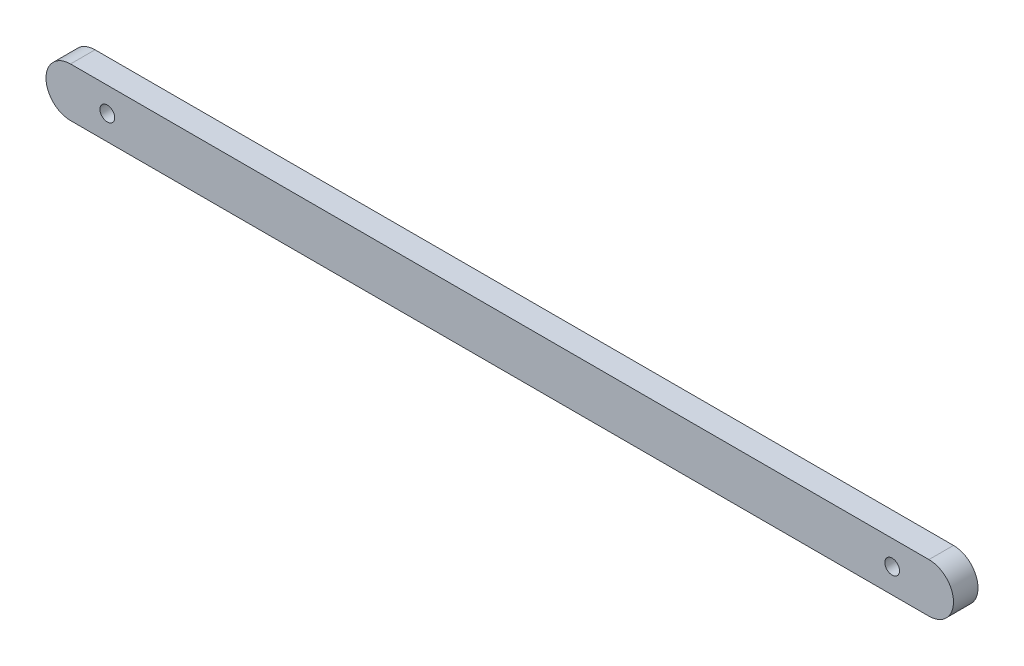
SolidWorks part; units mm, degrees
material "1023 Carbon Steel Sheet (SS)"
ref_plane "Ön Düzlem" through (0, 0, 0) normal (0, 0, 1) x (1, 0, 0)
ref_plane "Üst Düzlem" through (0, 0, 0) normal (0, 1, 0) x (1, 0, 0)
ref_plane "Sağ Düzlem" through (0, 0, 0) normal (1, 0, 0) x (0, 0, -1)
sketch "Sketch1" plane through (0, 0, 0) normal (0, 0, 1) x (1, 0, 0)
  line L4 (-175, 0) -> (175, 0) construction
  line L5 (-175, 10) -> (175, 10)
  line L6 (-175, -10) -> (175, -10)
  arc A0 (-175, 10) -> (-175, -10) centre (-175, 0) ccw
  arc A1 (175, -10) -> (175, 10) centre (175, 0) ccw
  point P3 (0, 0)
  point P8 (0, 0)
  dimension "D1" = 10
  dimension "D2" = 350
extrude "Boss-Extrude2" add sketch "Sketch1" along normal blind 10 contours A0 L6 A1 L5
sketch "Sketch3" plane through (0, 0, 10) normal (0, 0, 1) x (1, 0, 0)
  line L0 (-175, -10) -> (175, -10) construction
  line L2 (0, 0) -> (0, -10) construction
  circle A0 centre (-160, 0) radius 3
  arc A2 (-175, 10) -> (-175, -10) centre (-175, 0) ccw construction
  circle A3 centre (160, 0) radius 3
  point P5 (-185, 0)
  dimension "D1" = 6
  dimension "D2" = 25
  dimension "D3" = 10
extrude "Cut-Extrude2" cut sketch "Sketch3" against normal through all
